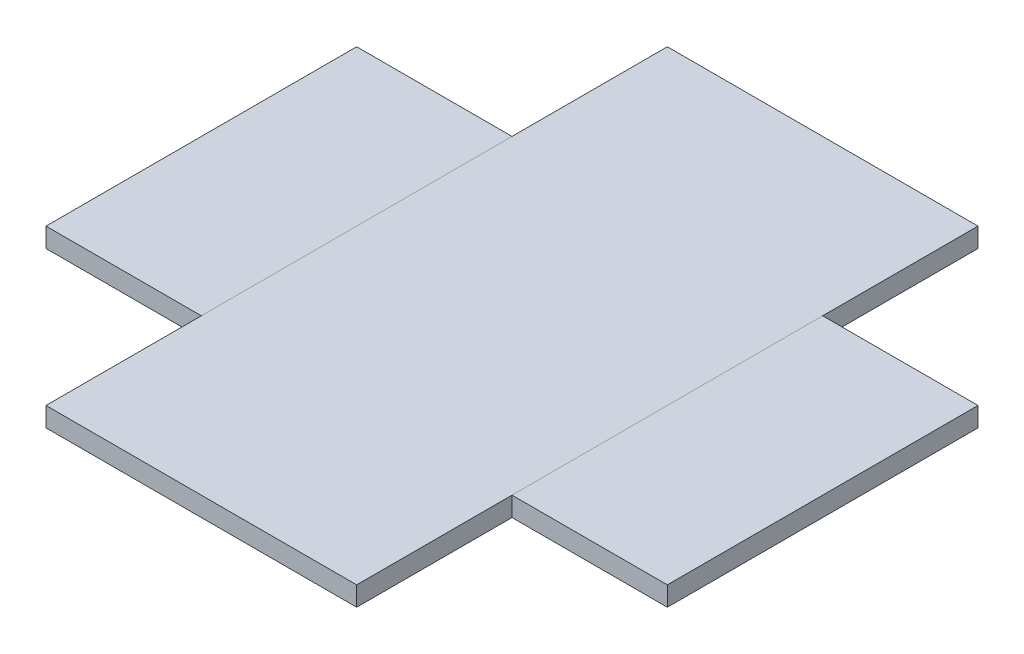
SolidWorks part; units mm, degrees
ref_plane "Front Plane" through (0, 0, 0) normal (0, 0, 1) x (1, 0, 0)
ref_plane "Top Plane" through (0, 0, 0) normal (0, 1, 0) x (1, 0, 0)
ref_plane "Right Plane" through (0, 0, 0) normal (1, 0, 0) x (0, 0, -1)
sketch "Sketch2" plane through (0, 0, 0) normal (0, 1, 0) x (1, 0, 0)
  line L1 (-50.8, -25.4) -> (50.8, -25.4)
  line L2 (-50.8, -25.4) -> (-50.8, 25.4)
  line L3 (-50.8, 25.4) -> (50.8, 25.4)
  line L4 (50.8, -25.4) -> (50.8, 25.4)
  line L5 (-50.8, -25.4) -> (50.8, 25.4) construction
  line L6 (-50.8, 25.4) -> (50.8, -25.4) construction
  point P0 (0, 0)
  dimension "D1" = 50.8
  dimension "D2" = 101.6
extrude "Boss-Extrude2" add sketch "Sketch2" along normal blind 3.175
sketch "Sketch3" plane through (0, 3.175, 0) normal (0, 1, 0) x (1, 0, 0)
  line L0 (50.8, -25.4) -> (50.8, 25.4) construction
  line L1 (-25.4, -50.8) -> (25.4, -50.8)
  line L2 (-25.4, -50.8) -> (-25.4, 50.8)
  line L3 (-25.4, 50.8) -> (25.4, 50.8)
  line L4 (25.4, -50.8) -> (25.4, 50.8)
  line L5 (-25.4, -50.8) -> (25.4, 50.8) construction
  line L6 (-25.4, 50.8) -> (25.4, -50.8) construction
  line L7 (50.8, 25.4) -> (-50.8, 25.4) construction
  point P0 (0, 0)
extrude "Boss-Extrude3" add sketch "Sketch3" against normal up to surface (3.175 mm away) separate body up to face at (0, 0, 0)
